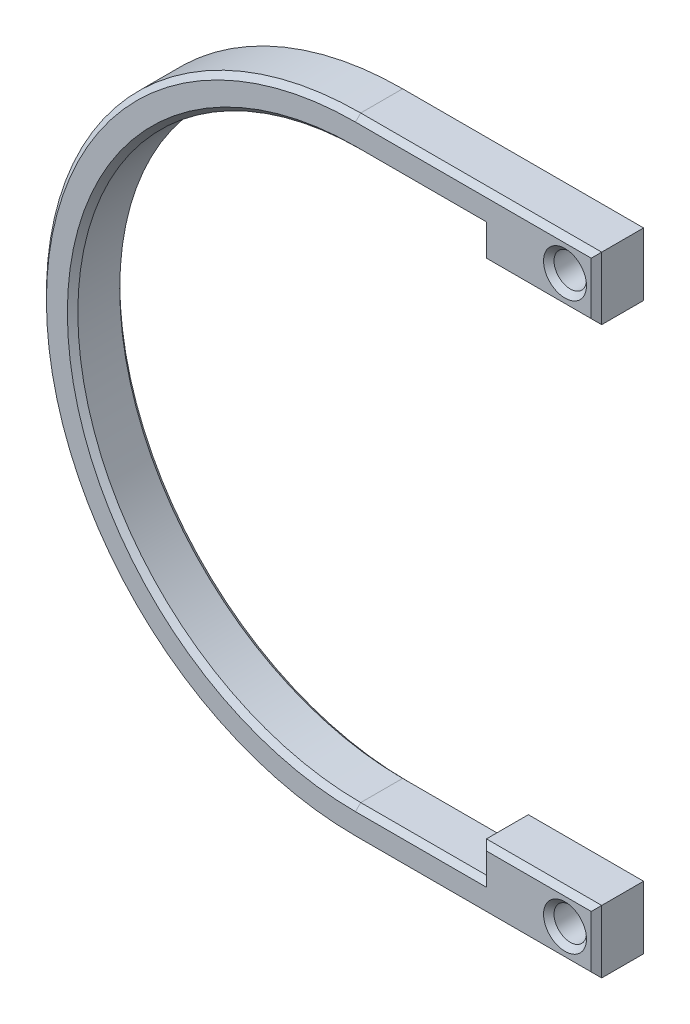
SolidWorks part; units mm, degrees
material "ABS"
ref_plane "正面" through (0, 0, 0) normal (0, 0, 1) x (1, 0, 0)
ref_plane "平面" through (0, 0, 0) normal (0, 1, 0) x (1, 0, 0)
ref_plane "右側面" through (0, 0, 0) normal (1, 0, 0) x (0, 0, -1)
sketch "ｽｹｯﾁ1" plane through (0, 0, 0) normal (0, 0, 1) x (1, 0, 0)
  line L0 (0, 30) -> (18, 30)
  line L1 (0, -30) -> (18, -30)
  line L2 (18, 30) -> (18, 24)
  line L3 (18, 24) -> (12, 24)
  line L4 (12, 24) -> (12, 27)
  line L5 (12, 27) -> (0, 27)
  line L6 (0, -27) -> (12, -27)
  line L7 (12, -27) -> (12, -24)
  line L8 (12, -24) -> (18, -24)
  line L9 (18, -24) -> (18, -30)
  arc A0 (0, 30) -> (0, -30) centre (0, 0) ccw
  arc A1 (0, 27) -> (0, -27) centre (0, 0) ccw
  dimension "D1" = 30
  dimension "D3" = 27
  dimension "D2" = 18
  dimension "D4" = 6
  dimension "D5" = 6
extrude "ﾎﾞｽ - 押し出し1" add sketch "ｽｹｯﾁ1" along normal blind 5
sketch "ｽｹｯﾁ3" plane through (0, 0, 5) normal (0, 0, 1) x (1, 0, 0)
  line L0 (12, 24) -> (18, 24) construction
  line L1 (23, -24) -> (18, -24)
  line L2 (23, -24) -> (23, -30)
  line L3 (23, -30) -> (18, -30)
  line L4 (18, -24) -> (18, -30)
  line L5 (23, -24) -> (18, -30) construction
  line L6 (23, -30) -> (18, -24) construction
  line L7 (23, 24) -> (18, 24)
  line L8 (23, 24) -> (23, 30)
  line L9 (23, 30) -> (18, 30)
  line L10 (18, 24) -> (18, 30)
  line L11 (23, 24) -> (18, 30) construction
  line L12 (23, 30) -> (18, 24) construction
  line L13 (18, -24) -> (12, -24) construction
  point P0 (20.5, -27)
  point P6 (20.5, 27)
  dimension "D1" = 5
extrude "ﾎﾞｽ - 押し出し2" add sketch "ｽｹｯﾁ3" against normal up to surface (5 mm away) up to face at (5.25, 0, 0)
sketch "ｽｹｯﾁ2" plane through (0, 0, 5) normal (0, 0, 1) x (1, 0, 0)
  line L0 (20, 24) -> (20, -24) construction
  line L3 (23, 30) -> (0, 30) construction
  line L4 (0, -30) -> (23, -30) construction
  line L5 (23, 24) -> (23, 30) construction
  line L6 (12, 24) -> (23, 24) construction
  line L7 (23, -24) -> (12, -24) construction
  circle A0 centre (20, -27) radius 1.55
  circle A1 centre (20, 27) radius 1.55
  dimension "D1" = 3
  dimension "D3" = 3.1
  dimension "D2" = 3
  dimension "D4" = 3
extrude "ｶｯﾄ - 押し出し1" cut sketch "ｽｹｯﾁ2" against normal through all
chamfer "面取り1" distance 0.5 angle 45 28 edges at (11.5, -30, 0) (23, -27, 0) (23, -27, 5) (17.5, -24, 0) (12, -25.5, 0) (6, -27, 0) (-27, 0, 0) (6, 27, 0) (12, 25.5, 0) (17.5, 24, 0) (23, 27, 0) (23, 27, 5) (11.5, 30, 0) (-30, 0, 0) (21.55, 27, 0) (21.55, -27, 0) (11.5, 30, 5) (17.5, 24, 5) (12, 25.5, 5) (6, 27, 5) (-27, 0, 5) (6, -27, 5) (12, -25.5, 5) (17.5, -24, 5) (11.5, -30, 5) (-30, 0, 5) (21.55, 27, 5) (21.55, -27, 5)
